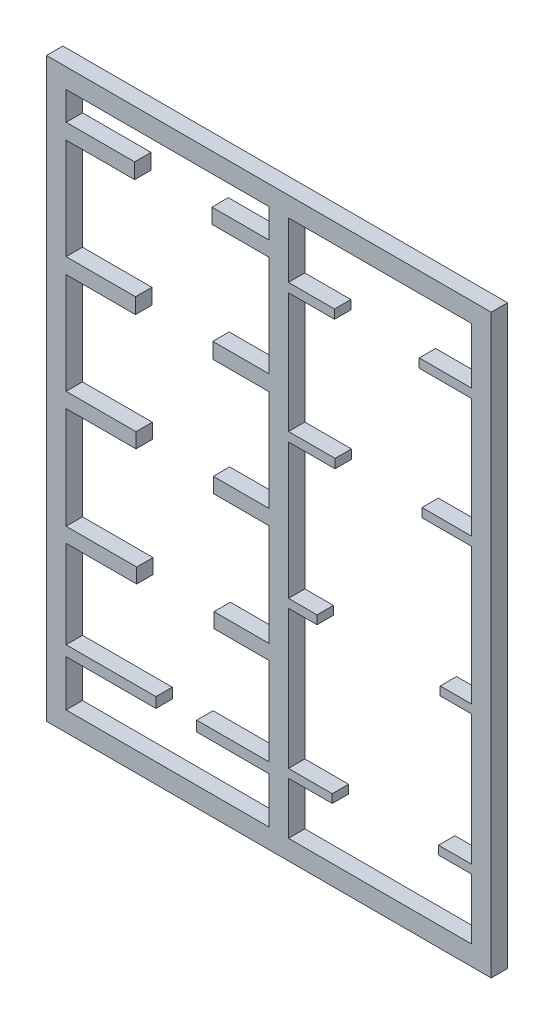
SolidWorks part; units mm, degrees
material "Plain Carbon Steel"
ref_plane "Front Plane" through (0, 0, 0) normal (0, 0, 1) x (1, 0, 0)
ref_plane "Top Plane" through (0, 0, 0) normal (0, 1, 0) x (1, 0, 0)
ref_plane "Right Plane" through (0, 0, 0) normal (1, 0, 0) x (0, 0, -1)
sketch "Sketch1" plane through (0, 0, 0) normal (0, 0, 1) x (1, 0, 0)
  line L0 (-91.1611, -22.5489) -> (-59.6965, -22.5489) construction
  line L1 (-94.2091, 62.2622) -> (-25.1838, 62.2622)
  line L2 (-94.2091, 62.2622) -> (-94.2091, -27.2393)
  line L3 (-94.2091, -27.2393) -> (-25.1838, -27.2393)
  line L4 (-25.1838, 62.2622) -> (-25.1838, -27.2393)
  line L5 (-91.1611, 59.2142) -> (-28.2318, 59.2142)
  line L6 (-91.1611, 59.2142) -> (-91.1611, -24.1913)
  line L7 (-91.1611, -24.1913) -> (-28.2318, -24.1913)
  line L8 (-28.2318, 59.2142) -> (-28.2318, -24.1913)
  line L9 (-59.6965, 59.2142) -> (-56.6485, 59.2142)
  line L10 (-59.6965, 59.2142) -> (-59.6965, -24.1913)
  line L11 (-59.6965, -24.1913) -> (-56.6485, -24.1913)
  line L12 (-56.6485, 59.2142) -> (-56.6485, -24.1913)
  line L13 (-59.6965, -22.5489) -> (-28.2318, -22.5489) construction
  line L14 (-36.3496, 49.0281) -> (-36.3496, 50.6778) construction
  line L15 (-36.3496, 49.1457) -> (-28.2318, 49.1457)
  line L16 (-36.3496, 49.1457) -> (-36.3496, 50.5367)
  line L17 (-36.3496, 50.5367) -> (-28.2318, 50.5367)
  line L18 (-28.2318, 49.1457) -> (-28.2318, 50.5367)
  line L19 (-35.768, 29.1411) -> (-35.9427, 30.8036) construction
  line L20 (-35.9249, 30.6341) -> (-28.2318, 30.6341)
  line L21 (-35.9249, 30.6341) -> (-35.9249, 29.2595)
  line L22 (-35.9249, 29.2595) -> (-28.2318, 29.2595)
  line L23 (-28.2318, 30.6341) -> (-28.2318, 29.2595)
  line L24 (-33.0899, 6.5696) -> (-33.0899, 8.1924) construction
  line L25 (-33.0899, 6.7317) -> (-28.2318, 6.7317)
  line L26 (-33.0899, 6.7317) -> (-33.0899, 8.0644)
  line L27 (-33.0899, 8.0644) -> (-28.2318, 8.0644)
  line L28 (-28.2318, 6.7317) -> (-28.2318, 8.0644)
  line L29 (-33.1736, -14.9201) -> (-33.3773, -13.2609) construction
  line L30 (-33.3522, -13.4657) -> (-28.2318, -13.4657)
  line L31 (-33.3522, -13.4657) -> (-33.3522, -14.7978)
  line L32 (-33.3522, -14.7978) -> (-28.2318, -14.7978)
  line L33 (-28.2318, -13.4657) -> (-28.2318, -14.7978)
  line L34 (-49.4992, 50.6778) -> (-49.4992, 49.0281) construction
  line L35 (-49.4992, 50.5367) -> (-56.6485, 50.5367)
  line L36 (-49.4992, 50.5367) -> (-49.4992, 49.1457)
  line L37 (-49.4992, 49.1457) -> (-56.6485, 49.1457)
  line L38 (-56.6485, 50.5367) -> (-56.6485, 49.1457)
  line L39 (-49.4153, 30.65) -> (-49.4153, 28.9784) construction
  line L40 (-49.4153, 30.4966) -> (-56.6485, 30.4966)
  line L41 (-49.4153, 30.4966) -> (-49.4153, 29.0905)
  line L42 (-49.4153, 29.0905) -> (-56.6485, 29.0905)
  line L43 (-56.6485, 30.4966) -> (-56.6485, 29.0905)
  line L44 (-52.2127, 8.1924) -> (-52.2127, 6.5696) construction
  line L45 (-52.2127, 8.0644) -> (-56.6485, 8.0644)
  line L46 (-52.2127, 8.0644) -> (-52.2127, 6.7317)
  line L47 (-52.2127, 6.7317) -> (-56.6485, 6.7317)
  line L48 (-56.6485, 8.0644) -> (-56.6485, 6.7317)
  line L49 (-49.8511, -14.5944) -> (-49.8511, -16.2661) construction
  line L50 (-49.8511, -14.7978) -> (-56.6485, -14.7978)
  line L51 (-49.8511, -14.7978) -> (-49.8511, -16.1182)
  line L52 (-49.8511, -16.1182) -> (-56.6485, -16.1182)
  line L53 (-56.6485, -14.7978) -> (-56.6485, -16.1182)
  line L54 (-68.5232, 54.9475) -> (-68.5232, 52.1603) construction
  line L55 (-68.5232, 54.7194) -> (-59.6965, 54.7194)
  line L56 (-68.5232, 54.7194) -> (-68.5232, 52.4029)
  line L57 (-68.5232, 52.4029) -> (-59.6965, 52.4029)
  line L58 (-59.6965, 54.7194) -> (-59.6965, 52.4029)
  line L59 (-68.393, 36.9765) -> (-68.393, 34.1893) construction
  line L60 (-68.393, 36.7388) -> (-59.6965, 36.7388)
  line L61 (-68.393, 36.7388) -> (-68.393, 34.3287)
  line L62 (-68.393, 34.3287) -> (-59.6965, 34.3287)
  line L63 (-59.6965, 36.7388) -> (-59.6965, 34.3287)
  line L64 (-68.3161, 18.8952) -> (-68.3161, 16.108) construction
  line L65 (-68.3161, 18.6378) -> (-59.6965, 18.6378)
  line L66 (-68.3161, 18.6378) -> (-68.3161, 16.3174)
  line L67 (-68.3161, 16.3174) -> (-59.6965, 16.3174)
  line L68 (-59.6965, 18.6378) -> (-59.6965, 16.3174)
  line L69 (-68.2064, 0.7551) -> (-68.2064, -2.0321) construction
  line L70 (-68.2064, 0.4957) -> (-59.6965, 0.4957)
  line L71 (-68.2064, 0.4957) -> (-68.2064, -1.7957)
  line L72 (-68.2064, -1.7957) -> (-59.6965, -1.7957)
  line L73 (-59.6965, 0.4957) -> (-59.6965, -1.7957)
  line L74 (-70.8904, -17.1407) -> (-70.8904, -15.3105) construction
  line L75 (-70.8904, -15.4302) -> (-59.6965, -15.4302)
  line L76 (-70.8904, -15.4302) -> (-70.8904, -17.0275)
  line L77 (-70.8904, -17.0275) -> (-59.6965, -17.0275)
  line L78 (-59.6965, -15.4302) -> (-59.6965, -17.0275)
  line L79 (-80.5232, 52.1603) -> (-80.5232, 54.9475) construction
  line L80 (-80.5232, 54.8032) -> (-91.1611, 54.8032)
  line L81 (-80.5232, 54.8032) -> (-80.5232, 52.4029)
  line L82 (-80.5232, 52.4029) -> (-91.1611, 52.4029)
  line L83 (-91.1611, 54.8032) -> (-91.1611, 52.4029)
  line L84 (-80.393, 34.1893) -> (-80.393, 36.9765) construction
  line L85 (-80.393, 36.7388) -> (-91.1611, 36.7388)
  line L86 (-80.393, 36.7388) -> (-80.393, 34.3287)
  line L87 (-80.393, 34.3287) -> (-91.1611, 34.3287)
  line L88 (-91.1611, 36.7388) -> (-91.1611, 34.3287)
  line L89 (-80.3161, 16.108) -> (-80.3161, 18.8952) construction
  line L90 (-80.3161, 18.6378) -> (-91.1611, 18.6378)
  line L91 (-80.3161, 18.6378) -> (-80.3161, 16.3174)
  line L92 (-80.3161, 16.3174) -> (-91.1611, 16.3174)
  line L93 (-91.1611, 18.6378) -> (-91.1611, 16.3174)
  line L94 (-80.2064, -2.0321) -> (-80.2064, 0.7551) construction
  line L95 (-80.2064, 0.4957) -> (-91.1611, 0.4957)
  line L96 (-80.2064, 0.4957) -> (-80.2064, -1.7957)
  line L97 (-80.2064, -1.7957) -> (-91.1611, -1.7957)
  line L98 (-91.1611, 0.4957) -> (-91.1611, -1.7957)
  line L99 (-77.2206, -15.3105) -> (-77.2206, -17.1407) construction
  line L100 (-77.2206, -15.4302) -> (-91.1611, -15.4302)
  line L101 (-77.2206, -15.4302) -> (-77.2206, -17.0275)
  line L102 (-77.2206, -17.0275) -> (-91.1611, -17.0275)
  line L103 (-91.1611, -15.4302) -> (-91.1611, -17.0275)
  dimension "D1" = 3.048
  dimension "D2" = 3.048
  dimension "D3" = 3.048
  dimension "D4" = 3.048
  dimension "D5" = 3.048
extrude "Boss-Extrude1" add sketch "Sketch1" along normal blind 2.54 contours L4 L1 L2 L3 L5 L8 L7 L6 | L82 L81 L80 L6 | L87 L86 L85 L6 | L92 L91 L90 L6 | L66 L67 L10 L65 | L61 L62 L10 L60 | L12 L5 L10 L7 | L42 L41 L40 L12 | L21 L22 L8 L20 | L27 L26 L25 L8 | L31 L32 L8 L30 | L52 L51 L50 L12 | L95 L98 L97 L96 | L100 L103 L102 L101 | L77 L78 L75 L76 | L72 L73 L70 L71 | L55 L58 L57 L56 | L15 L18 L17 L16 | L35 L38 L37 L36 | L45 L48 L47 L46
